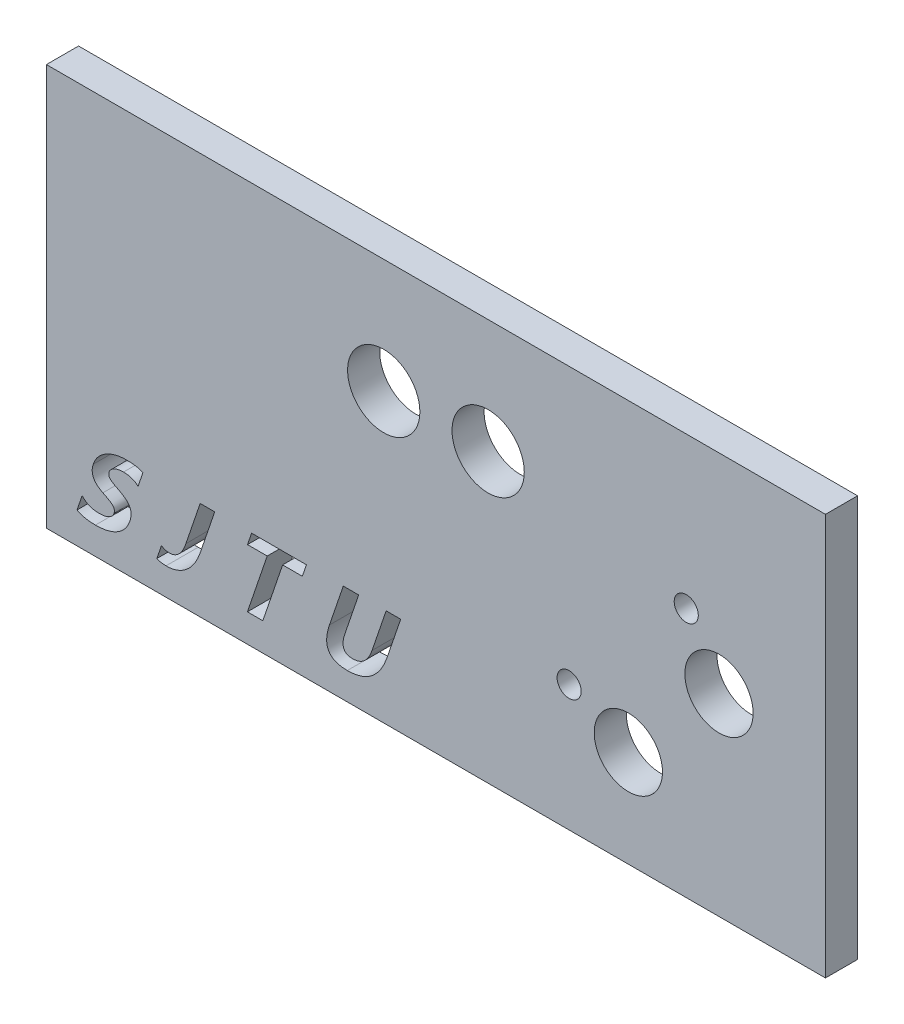
SolidWorks part; units mm, degrees
ref_plane "前视基准面" through (0, 0, 0) normal (0, 0, 1) x (1, 0, 0)
ref_plane "上视基准面" through (0, 0, 0) normal (0, 1, 0) x (1, 0, 0)
ref_plane "右视基准面" through (0, 0, 0) normal (1, 0, 0) x (0, 0, -1)
sketch "草图1" plane through (0, 0, 0) normal (0, 0, 1) x (1, 0, 0)
  line L0 (134.6674, -31.3911) -> (100.0032, 30.9661) construction
  line L1 (-59.3326, 68.6089) -> (134.6674, 68.6089)
  line L2 (-59.3326, 68.6089) -> (-59.3326, -31.3911)
  line L3 (-59.3326, -31.3911) -> (134.6674, -31.3911)
  line L4 (134.6674, 68.6089) -> (134.6674, -31.3911)
  line L5 (134.6674, -31.3911) -> (70.8349, -0.0151) construction
  line L6 (37.6674, 68.6089) -> (37.6674, -31.3911) construction
  circle A0 centre (100.0032, 30.9661) radius 3
  circle A1 centre (70.8349, -0.0151) radius 3
  circle A2 centre (85.5812, -7.2642) radius 8.5
  circle A3 centre (108.1558, 16.6992) radius 8.5
  circle A6 centre (24.6674, 40.2002) radius 9
  circle A7 centre (50.6674, 40.2002) radius 9
  text T0 "S J T U" font "微软雅黑" height 17.5
  dimension "D3" = 6
  dimension "D4" = 6
  dimension "D5" = 17
  dimension "D6" = 17
  dimension "D7" = 18
  dimension "D8" = 18
  dimension "D9" = 26
  dimension "D1" = 194
  dimension "D2" = 100
  dimension "D10" = 13
extrude "凸台-拉伸1" add sketch "草图1" along normal blind 8
